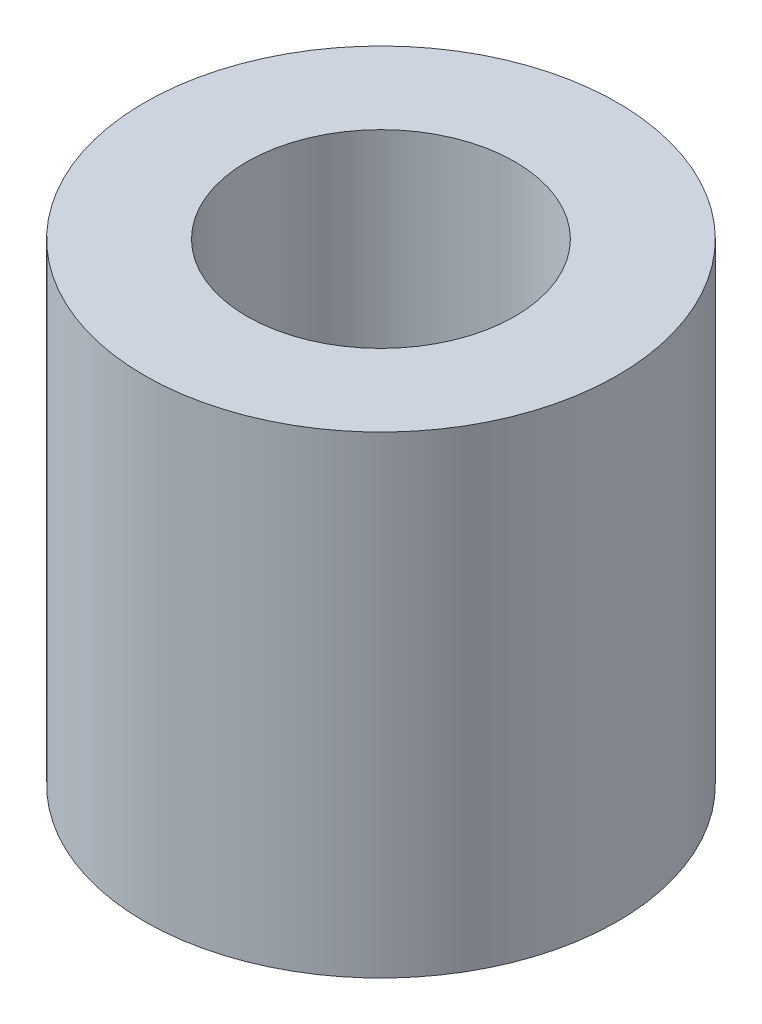
SolidWorks part; units mm, degrees
ref_plane "Front Plane" through (0, 0, 0) normal (0, 0, 1) x (1, 0, 0)
ref_plane "Top Plane" through (0, 0, 0) normal (0, 1, 0) x (1, 0, 0)
ref_plane "Right Plane" through (0, 0, 0) normal (1, 0, 0) x (0, 0, -1)
sketch "Sketch1" plane through (0, 0, 0) normal (0, 1, 0) x (1, 0, 0)
  circle A0 centre (0, 0) radius 3
  dimension "D1" = 6
extrude "Boss-Extrude1" add sketch "Sketch1" along normal blind 6
hole_wizard "M3 Clearance Hole1" positions "Sketch4" profile "Sketch3" hole size "M3" standard "ANSI Metric" end condition through all
sketch "Sketch4" plane through (0, 6, 0) normal (0, 1, 0) x (1, 0, 0)
  point P0 (0, 0)
sketch "Sketch3" plane through (0, 6, 0) normal (1, 0, 0) x (0, 0, 1)
  line L0 (0, 0) -> (0, 6)
  line L1 (0, 6) -> (1.7, 6)
  line L2 (1.7, 6) -> (1.7, 0)
  line L5 (1.7, 0) -> (0, 0)
  line L11 (0, -6.35) -> (0, 107.95) construction
  dimension "Thru Hole Dia." = 3.4
  dimension "Thru Hole Depth" = 6
